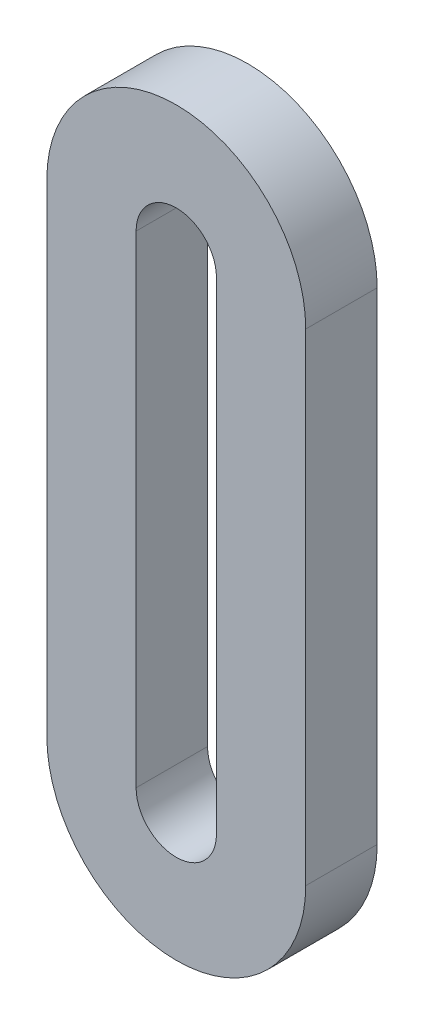
SolidWorks part; units mm, degrees
ref_plane "Front Plane" through (0, 0, 0) normal (0, 0, 1) x (1, 0, 0)
ref_plane "Top Plane" through (0, 0, 0) normal (0, 1, 0) x (1, 0, 0)
ref_plane "Right Plane" through (0, 0, 0) normal (1, 0, 0) x (0, 0, -1)
sketch "Sketch1" plane through (0, 0, 0) normal (0, 0, 1) x (1, 0, 0)
  line L0 (0, 13.5) -> (0, -13.5) construction
  line L1 (2.25, 13.5) -> (2.25, -13.5)
  line L2 (-2.25, 13.5) -> (-2.25, -13.5)
  line L3 (7.25, 13.5) -> (7.25, -13.5)
  line L4 (-7.25, 13.5) -> (-7.25, -13.5)
  arc A0 (2.25, 13.5) -> (-2.25, 13.5) centre (0, 13.5) ccw
  arc A1 (-2.25, -13.5) -> (2.25, -13.5) centre (0, -13.5) ccw
  arc A2 (-7.25, -13.5) -> (7.25, -13.5) centre (0, -13.5) ccw
  arc A3 (7.25, 13.5) -> (-7.25, 13.5) centre (0, 13.5) ccw
  point P3 (0, 0)
  point P8 (0, 0)
  dimension "D1" = 4.5
  dimension "D2" = 27
  dimension "D3" = 5
extrude "Boss-Extrude1" add sketch "Sketch1" along normal blind 4
